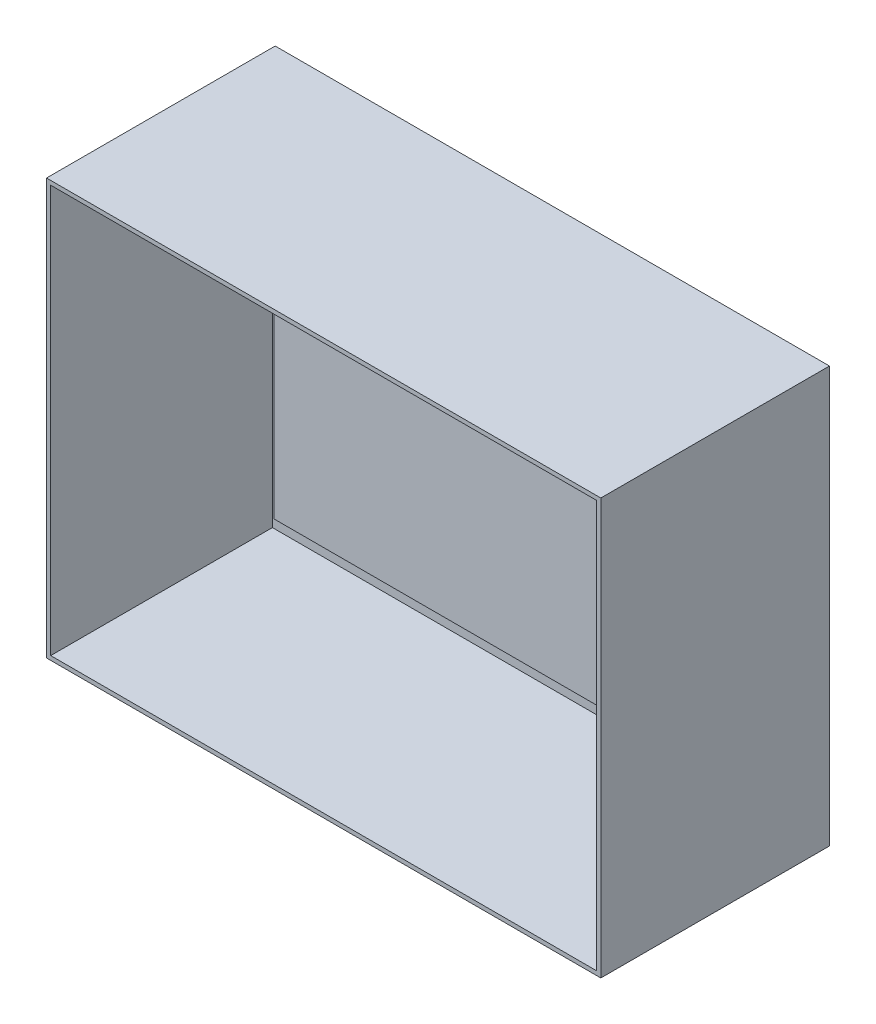
SolidWorks part; units mm, degrees
ref_plane "Front Plane" through (0, 0, 0) normal (0, 0, 1) x (1, 0, 0)
ref_plane "Top Plane" through (0, 0, 0) normal (0, 1, 0) x (1, 0, 0)
ref_plane "Right Plane" through (0, 0, 0) normal (1, 0, 0) x (0, 0, -1)
sketch "Sketch1" plane through (0, 0, 0) normal (0, 0, 1) x (1, 0, 0)
  line L1 (-200, 150) -> (200, 150)
  line L2 (-200, 150) -> (-200, -150)
  line L3 (-200, -150) -> (200, -150)
  line L4 (200, 150) -> (200, -150)
  line L5 (-200, 150) -> (200, -150) construction
  line L6 (-200, -150) -> (200, 150) construction
  point P0 (0, 0)
  dimension "D1" = 400
  dimension "D2" = 300
extrude "Boss-Extrude1" add sketch "Sketch1" along normal blind 5
sketch "Sketch2" plane through (0, 0, 0) normal (0, 0, 1) x (1, 0, 0)
  line L1 (-200, 150) -> (200, 150)
  line L2 (-200, 150) -> (-200, -150)
  line L3 (-200, -150) -> (200, -150)
  line L4 (200, 150) -> (200, -150)
  line L5 (-197, 147) -> (197, 147)
  line L6 (-197, 147) -> (-197, -147)
  line L7 (-197, -147) -> (197, -147)
  line L8 (197, 147) -> (197, -147)
  dimension "D1" = 3
  dimension "D2" = 3
  dimension "D3" = 3
  dimension "D4" = 3
extrude "Boss-Extrude2" add sketch "Sketch2" along normal blind 165
sketch "Sketch3" plane through (0, 0, 0) normal (0, 0, 1) x (1, 0, 0)
  line L1 (-175, 120) -> (175, 120)
  line L2 (-175, 120) -> (-175, -120)
  line L3 (-175, -120) -> (175, -120)
  line L4 (175, 120) -> (175, -120)
  line L5 (-175, 120) -> (175, -120) construction
  line L6 (-175, -120) -> (175, 120) construction
  point P0 (0, 0)
  dimension "D1" = 350
  dimension "D2" = 240
extrude "Boss-Extrude3" add sketch "Sketch3" along normal blind 26
